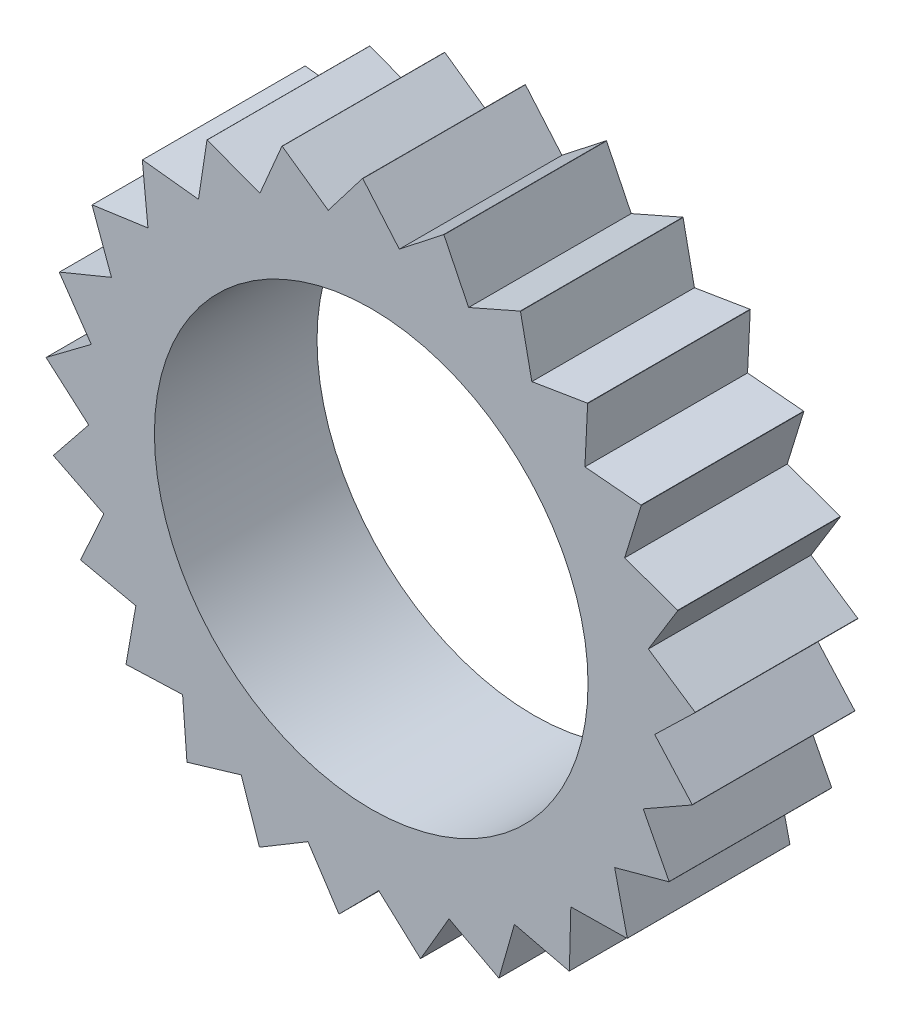
SolidWorks part; units mm, degrees
ref_plane "Plan de face" through (0, 0, 0) normal (0, 0, 1) x (1, 0, 0)
ref_plane "Plan de dessus" through (0, 0, 0) normal (0, 1, 0) x (1, 0, 0)
ref_plane "Plan de droite" through (0, 0, 0) normal (1, 0, 0) x (0, 0, -1)
sketch "Esquisse1" plane through (0, 0, 0) normal (0, 0, 1) x (1, 0, 0)
  circle A0 centre (0, 0) radius 6
  circle A1 centre (0, 0) radius 4
extrude "Boss.-Extru.1" add sketch "Esquisse1" along normal blind 3
sketch "Esquisse2" plane through (0, 0, 3) normal (0, 0, 1) x (1, 0, 0)
  line L0 (-1.6435, 5.7705) -> (-1.6422, 5.7707)
  line L2 (-0.7931, 5.1725) -> (-1.6435, 5.7705)
  line L3 (-1.6435, 5.7705) -> (-1.6437, 5.7717)
  line L5 (-2.4942, 6.371) -> (-0.7931, 5.1725)
  line L7 (0.4714, 6.8232) -> (-0.7931, 5.1725)
  line L8 (-2.4942, 6.371) -> (0.4714, 6.8232)
  line L9 (0.4714, 6.8232) -> (0.4707, 6.8179)
  circle A0 centre (0, 0) radius 6 construction
  point P10 (-1.6437, 5.7717)
  point P13 (-0.1609, 5.9978)
  dimension "D1" = 0.72
extrude "Enlèv. mat.-Extru.1" cut sketch "Esquisse2" against normal blind 3
pattern_circular "Répétition circulaire1" count 25 over 360 about axis through (0, 0, 0) along (0, 0, 1) of "Enlèv. mat.-Extru.1"
